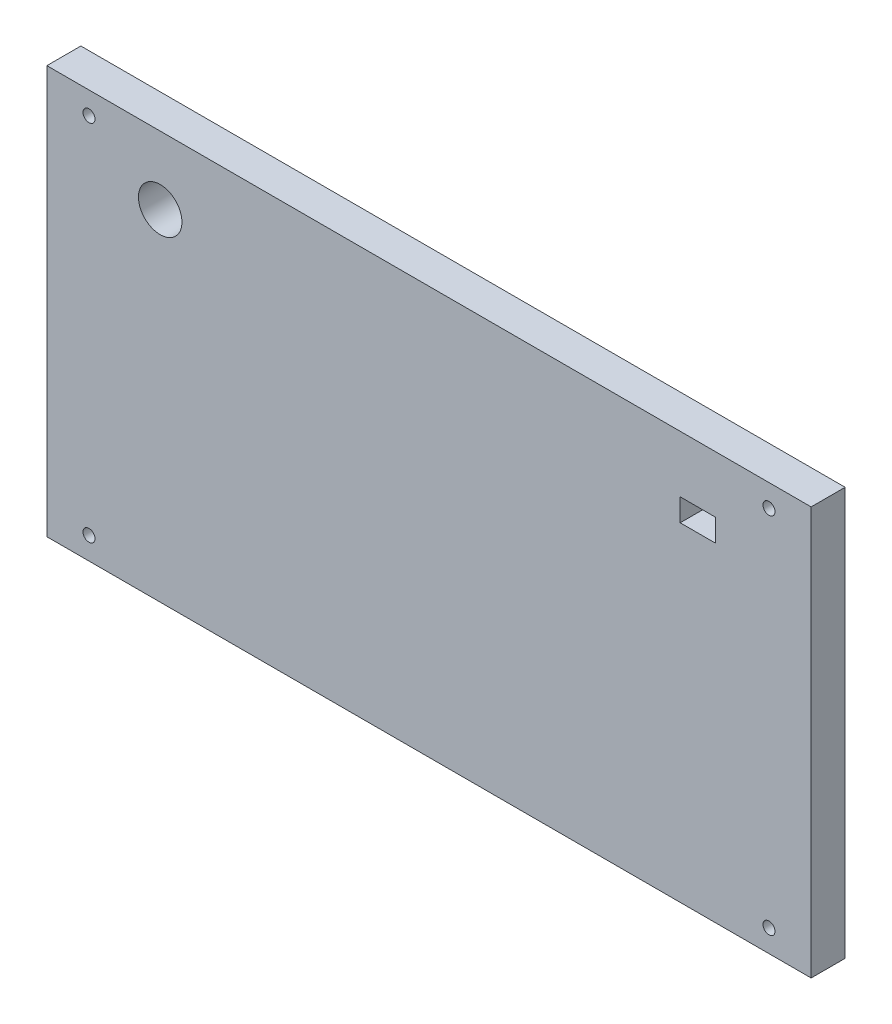
SolidWorks part; units mm, degrees
ref_plane "Front Plane" through (0, 0, 0) normal (0, 0, 1) x (1, 0, 0)
ref_plane "Top Plane" through (0, 0, 0) normal (0, 1, 0) x (1, 0, 0)
ref_plane "Right Plane" through (0, 0, 0) normal (1, 0, 0) x (0, 0, -1)
sketch "Sketch1" plane through (0, 0, 0) normal (0, 0, 1) x (1, 0, 0)
  line L0 (385.3879, -36.1125) -> (391.5371, -36.1125) construction
  line L1 (-23.6125, 192.4875) -> (404.6125, 192.4875)
  line L2 (-23.6125, 192.4875) -> (-23.6125, -36.1125)
  line L3 (-23.6125, -36.1125) -> (404.6125, -36.1125)
  line L4 (404.6125, 192.4875) -> (404.6125, -36.1125)
  line L5 (-23.6125, 78.1875) -> (404.6125, 78.1875) construction
  line L6 (190.5, 560.9629) -> (190.5, -131.2692) construction
  line L7 (368.5, 560.9629) -> (12.5, 560.9629) construction
  circle A0 centre (0, -23.6125) radius 3.3655
  circle A1 centre (381, -23.6125) radius 3.3655
  circle A2 centre (381, 179.9875) radius 3.3655
  circle A3 centre (0, 179.9875) radius 3.3655
  circle A4 centre (39.8875, 154.3875) radius 12.192
  point P7 (190.5, 192.4875)
  dimension "D1" = 6.731
  dimension "D2" = 24.384
  dimension "D3" = 38.1
  dimension "D4" = 63.5
extrude "Boss-Extrude1" add sketch "Sketch1" along normal blind 19.05
sketch "Sketch2" plane through (0, 0, 19.05) normal (0, 0, 1) x (1, 0, 0)
  line L0 (341.1125, 192.4875) -> (341.1125, -36.1125) construction
  line L3 (12.5, 192.4875) -> (368.5, 192.4875) construction
  line L4 (331.2375, 148.0875) -> (350.9875, 148.0875)
  line L5 (331.2375, 148.0875) -> (331.2375, 160.6875)
  line L6 (331.2375, 160.6875) -> (350.9875, 160.6875)
  line L7 (350.9875, 148.0875) -> (350.9875, 160.6875)
  line L8 (331.2375, 148.0875) -> (350.9875, 160.6875) construction
  line L9 (331.2375, 160.6875) -> (350.9875, 148.0875) construction
  line L10 (-23.6125, -36.1125) -> (404.6125, -36.1125) construction
  line L11 (404.6125, -36.1125) -> (404.6125, 192.4875) construction
  line L12 (404.6125, 192.4875) -> (-23.6125, 192.4875) construction
  point P6 (341.1125, 154.3875)
  dimension "D1" = 19.75
  dimension "D2" = 12.6
  dimension "D3" = 63.5
  dimension "D4" = 38.1
extrude "Cut-Extrude1" cut sketch "Sketch2" against normal through all
